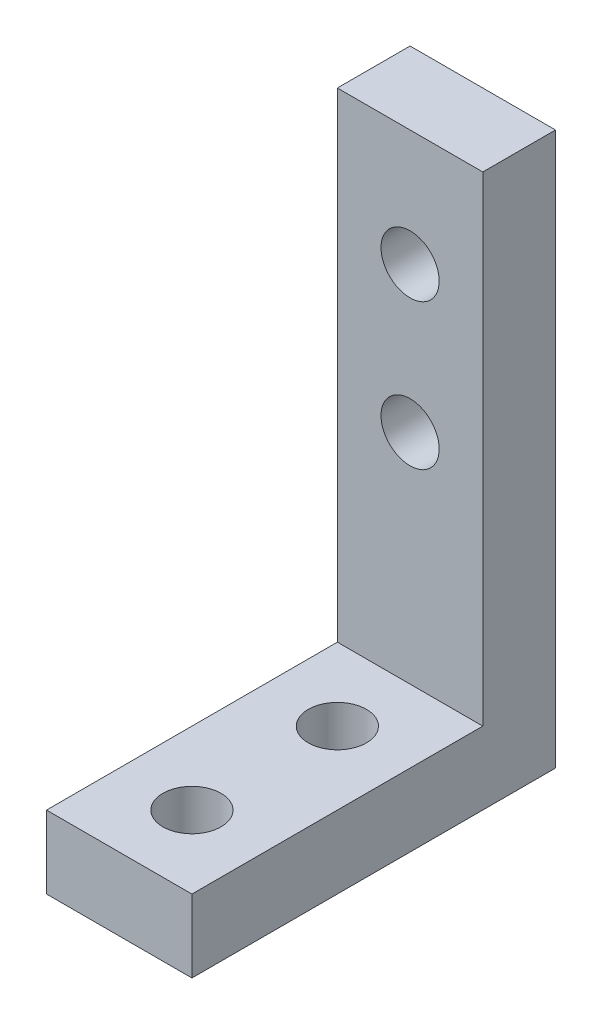
SolidWorks part; units mm, degrees
ref_plane "Front Plane" through (0, 0, 0) normal (0, 0, 1) x (1, 0, 0)
ref_plane "Top Plane" through (0, 0, 0) normal (0, 1, 0) x (1, 0, 0)
ref_plane "Right Plane" through (0, 0, 0) normal (1, 0, 0) x (0, 0, -1)
sketch "Sketch2" plane through (0, 0, 0) normal (0, 1, 0) x (1, 0, 0)
  line L1 (-5, -12.5) -> (5, -12.5)
  line L2 (-5, -12.5) -> (-5, 12.5)
  line L3 (-5, 12.5) -> (5, 12.5)
  line L4 (5, -12.5) -> (5, 12.5)
  line L5 (-5, -12.5) -> (5, 12.5) construction
  line L6 (-5, 12.5) -> (5, -12.5) construction
  point P0 (0, 0)
  dimension "D1" = 10
  dimension "D2" = 25
extrude "Boss-Extrude1" add sketch "Sketch2" along normal blind 5
sketch "Sketch4" plane through (0, 5, 0) normal (0, 1, 0) x (1, 0, 0)
  line L0 (-5, 12.5) -> (-5, -12.5) construction
  line L1 (5, 12.5) -> (-5, 12.5)
  line L2 (5, 12.5) -> (5, 7.5)
  line L3 (5, 7.5) -> (-5, 7.5)
  line L4 (-5, 12.5) -> (-5, 7.5)
  dimension "D1" = 5
extrude "Boss-Extrude2" add sketch "Sketch4" along normal blind 33
sketch "Sketch6" plane through (0, 5, 0) normal (0, 1, 0) x (1, 0, 0)
  line L0 (-5, 7.5) -> (-5, -12.5) construction
  line L1 (-5, -12.5) -> (5, -12.5) construction
  circle A0 centre (0, 2.5) radius 2
  circle A1 centre (0, -7.5) radius 2
  dimension "D4" = 4
  dimension "D5" = 4
  dimension "D1" = 5
  dimension "D2" = 5
  dimension "D3" = 5
  dimension "D6" = 10
extrude "Cut-Extrude1" cut sketch "Sketch6" against normal through all
sketch "Sketch7" plane through (0, 0, -7.5) normal (0, 0, 1) x (1, 0, 0)
  line L1 (5, 38) -> (5, 5) construction
  line L2 (-5, 0) -> (5, 0) construction
  circle A0 centre (0, 30) radius 2
  circle A1 centre (0, 20) radius 2
  dimension "D3" = 4
  dimension "D4" = 4
  dimension "D1" = 5
  dimension "D2" = 5
  dimension "D5" = 10
  dimension "D6" = 20
extrude "Cut-Extrude2" cut sketch "Sketch7" against normal through all
